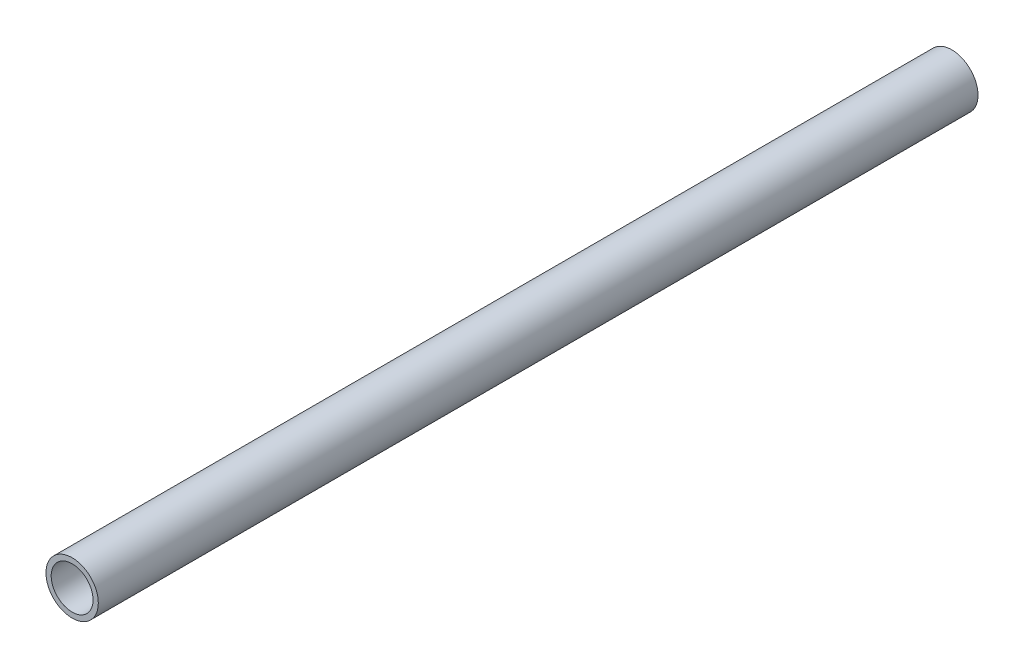
SolidWorks part; units mm, degrees
ref_plane "Front Plane" through (0, 0, 0) normal (0, 0, 1) x (1, 0, 0)
ref_plane "Top Plane" through (0, 0, 0) normal (0, 1, 0) x (1, 0, 0)
ref_plane "Right Plane" through (0, 0, 0) normal (1, 0, 0) x (0, 0, -1)
sketch "Sketch1" plane through (0, 0, 0) normal (0, 0, 1) x (1, 0, 0)
  circle A0 centre (0, 0) radius 15.875
  circle A1 centre (0, 0) radius 12.7
  dimension "D1" = 31.75
  dimension "D2" = 25.4
extrude "Boss-Extrude1" add sketch "Sketch1" along normal blind 533.4
